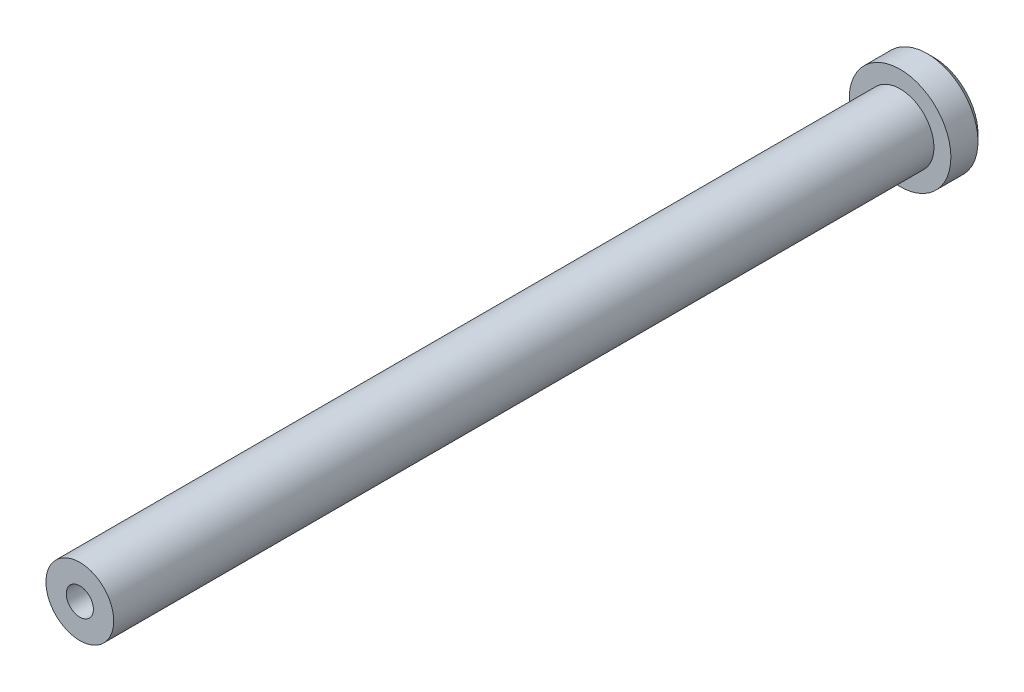
SolidWorks part; units mm, degrees
ref_plane "Front Plane" through (0, 0, 0) normal (0, 0, 1) x (1, 0, 0)
ref_plane "Top Plane" through (0, 0, 0) normal (0, 1, 0) x (1, 0, 0)
ref_plane "Right Plane" through (0, 0, 0) normal (1, 0, 0) x (0, 0, -1)
sketch "Sketch2" plane through (0, 0, 0) normal (0, 0, 1) x (1, 0, 0)
  circle A0 centre (0, 0) radius 7.5
  dimension "D1" = 15
extrude "Boss-Extrude1" add sketch "Sketch2" along normal blind 5
chamfer "Chamfer1" distance 1 angle 45 1 edges at (7.5, 0, 0)
sketch "Sketch3" plane through (0, 0, 5) normal (0, 0, 1) x (1, 0, 0)
  circle A0 centre (0, 0) radius 5
  dimension "D1" = 10
extrude "Boss-Extrude2" add sketch "Sketch3" along normal blind 121
sketch "Sketch4" plane through (0, 0, 126) normal (0, 0, 1) x (1, 0, 0)
  circle A0 centre (0, 0) radius 2
  dimension "D1" = 4
extrude "Cut-Extrude1" cut sketch "Sketch4" against normal blind 10
